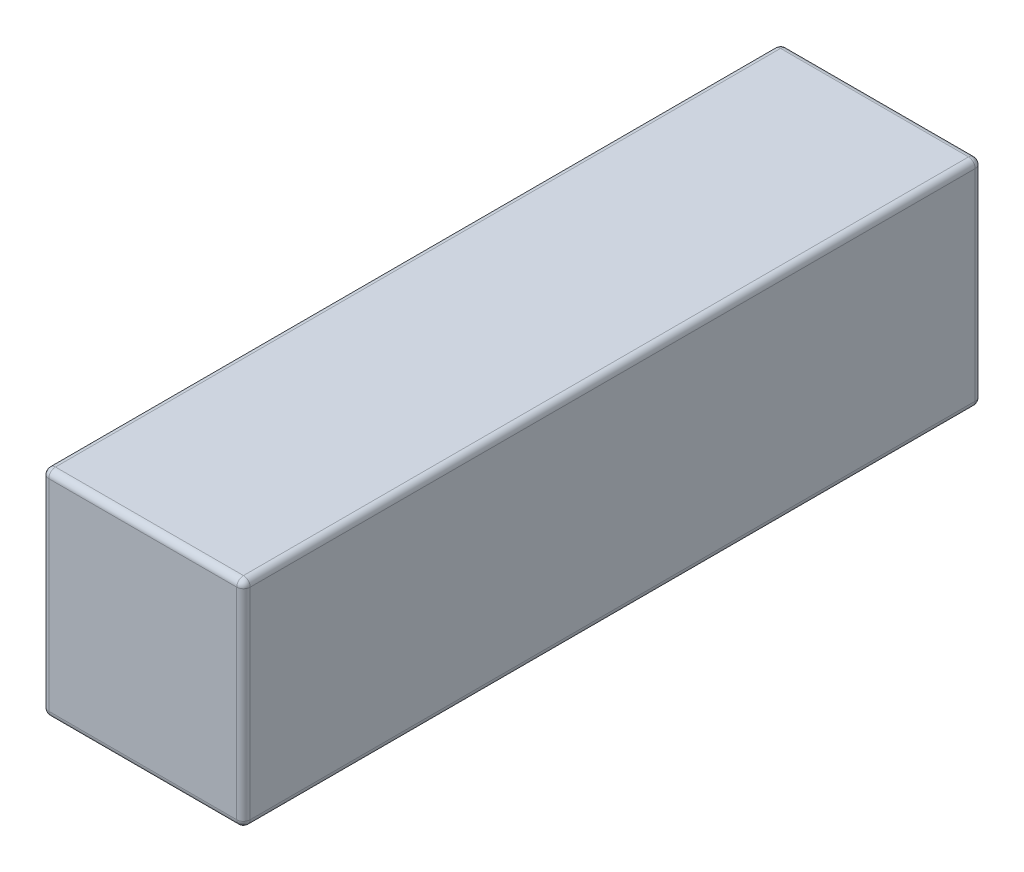
SolidWorks part; units mm, degrees
ref_plane "Front Plane" through (0, 0, 0) normal (0, 0, 1) x (1, 0, 0)
ref_plane "Top Plane" through (0, 0, 0) normal (0, 1, 0) x (1, 0, 0)
ref_plane "Right Plane" through (0, 0, 0) normal (1, 0, 0) x (0, 0, -1)
sketch "Sketch1" plane through (0, 0, 0) normal (0, 1, 0) x (1, 0, 0)
  line L1 (15, -59.5536) -> (-15, -59.5536)
  line L2 (15, -59.5536) -> (15, 50.4464)
  line L3 (15, 50.4464) -> (-15, 50.4464)
  line L4 (-15, -59.5536) -> (-15, 50.4464)
  line L5 (15, -59.5536) -> (-15, 50.4464) construction
  line L6 (15, 50.4464) -> (-15, -59.5536) construction
  point P0 (0, -4.5536)
  dimension "D1" = 30
  dimension "D2" = 110
extrude "Boss-Extrude1" add sketch "Sketch1" along normal blind 32
fillet "Fillet1" radius 1 12 edges at (0, 0, -50.4464) (-15, 16, -50.4464) (-15, 0, 4.5536) (-15, 16, 59.5536) (0, 0, 59.5536) (0, 32, -50.4464) (0, 32, 59.5536) (-15, 32, 4.5536) (15, 16, 59.5536) (15, 32, 4.5536) (15, 16, -50.4464) (15, 0, 4.5536)
